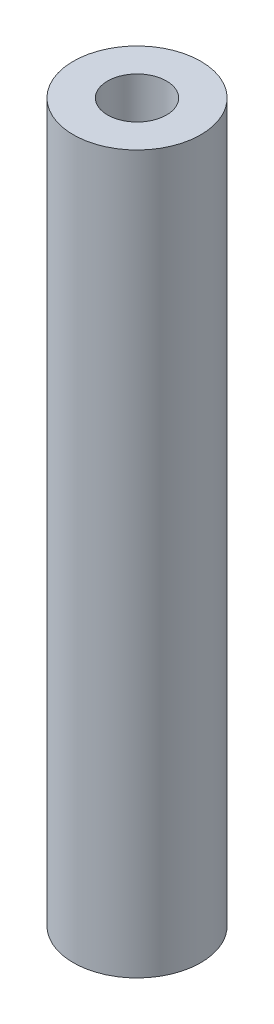
SolidWorks part; units mm, degrees
ref_plane "前视基准面" through (0, 0, 0) normal (0, 0, 1) x (1, 0, 0)
ref_plane "上视基准面" through (0, 0, 0) normal (0, 1, 0) x (1, 0, 0)
ref_plane "右视基准面" through (0, 0, 0) normal (1, 0, 0) x (0, 0, -1)
other "Configuration Table"
sketch "草图1" plane through (0, 0, 0) normal (0, 1, 0) x (1, 0, 0)
  circle A0 centre (0, 0) radius 4
  circle A1 centre (0, 0) radius 1.85
  dimension "D1" = 3.7
  dimension "D2" = 8
extrude "凸台-拉伸1" add sketch "草图1" along normal blind 45
